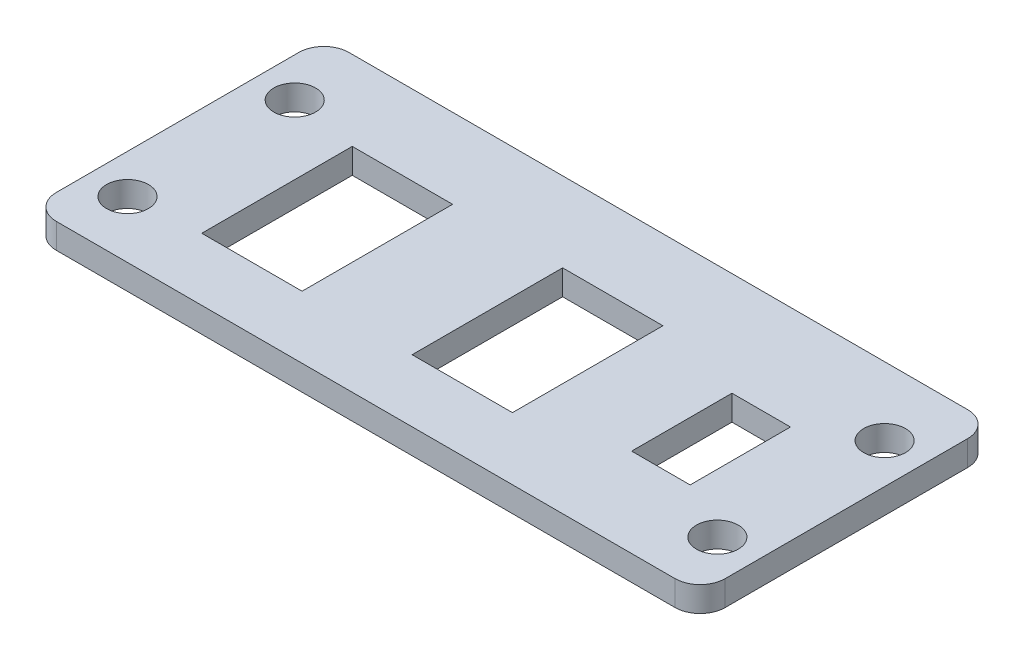
SolidWorks part; units mm, degrees
ref_plane "Front Plane" through (0, 0, 0) normal (0, 0, 1) x (1, 0, 0)
ref_plane "Top Plane" through (0, 0, 0) normal (0, 1, 0) x (1, 0, 0)
ref_plane "Right Plane" through (0, 0, 0) normal (1, 0, 0) x (0, 0, -1)
sketch "Sketch1" plane through (0, 0, 0) normal (0, 1, 0) x (1, 0, 0)
  line L0 (309.2205, -72.6297) -> (321.2205, -72.6297)
  line L1 (271.1347, -98.0957) -> (351.1347, -98.0957)
  line L2 (271.1347, -98.0957) -> (271.1347, -63.0957)
  line L3 (271.1347, -63.0957) -> (351.1347, -63.0957)
  line L4 (351.1347, -98.0957) -> (351.1347, -63.0957)
  line L5 (284.0625, -72.6297) -> (296.0625, -72.6297)
  line L6 (284.0625, -72.6297) -> (284.0625, -90.6297)
  line L7 (284.0625, -90.6297) -> (296.0625, -90.6297)
  line L8 (296.0625, -72.6297) -> (296.0625, -90.6297)
  line L9 (309.2205, -72.6297) -> (309.2205, -90.6297)
  line L10 (309.2205, -90.6297) -> (321.2205, -90.6297)
  line L11 (321.2205, -72.6297) -> (321.2205, -90.6297)
  line L13 (332.3348, -75.4891) -> (339.3348, -75.4891)
  line L14 (332.3348, -75.4891) -> (332.3348, -87.4891)
  line L15 (332.3348, -87.4891) -> (339.3348, -87.4891)
  line L16 (339.3348, -75.4891) -> (339.3348, -87.4891)
  circle A0 centre (275.8183, -71.2683) radius 2.5
  circle A1 centre (275.8183, -91.2683) radius 2.5
  circle A2 centre (346.3705, -71.2683) radius 2.5
  circle A3 centre (346.3705, -91.2683) radius 2.5
  dimension "D3" = 5
  dimension "D1" = 80
  dimension "D2" = 35
  dimension "D4" = 20
  dimension "D5" = 18
  dimension "D6" = 12
  dimension "D7" = 12
  dimension "D8" = 7
extrude "Boss-Extrude1" add sketch "Sketch1" along normal blind 3
fillet "Fillet1" radius 3 4 edges at (271.1347, 1.5, 98.0957) (271.1347, 1.5, 63.0957) (351.1347, 1.5, 63.0957) (351.1347, 1.5, 98.0957)
